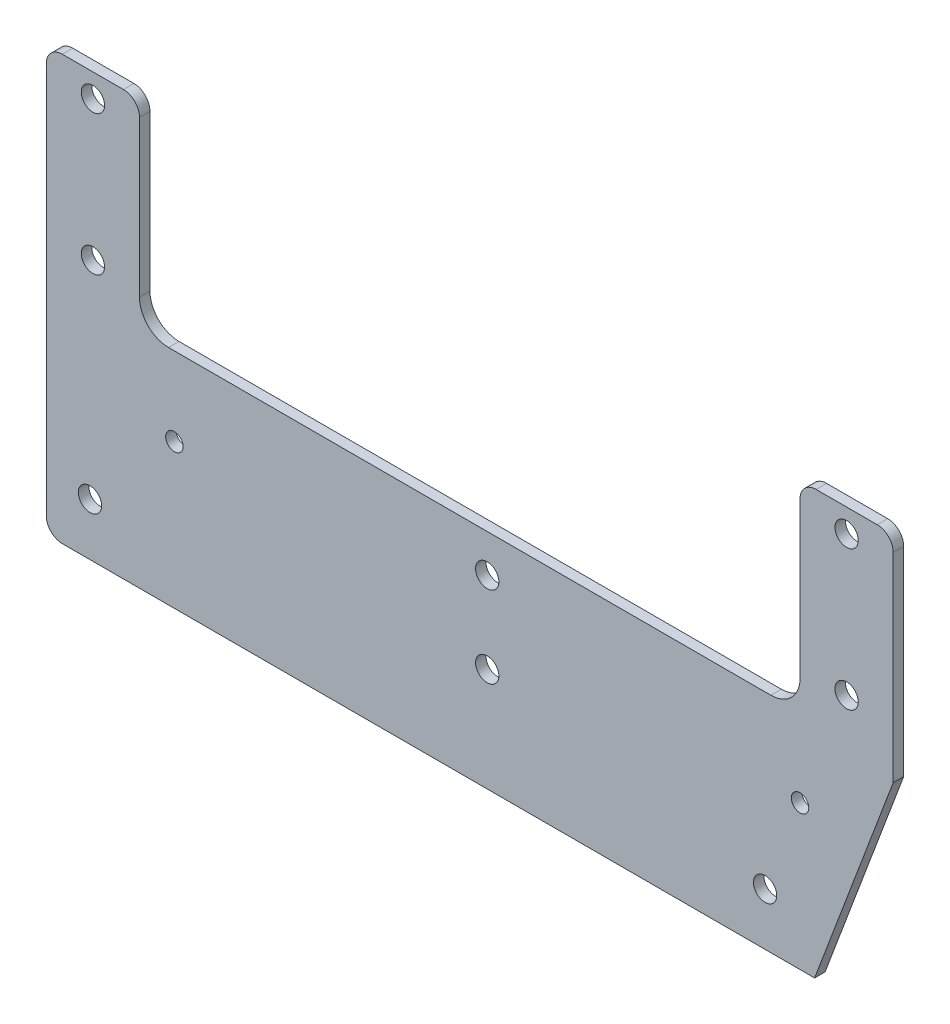
SolidWorks part; units mm, degrees
ref_plane "前视基准面" through (0, 0, 0) normal (0, 0, 1) x (1, 0, 0)
ref_plane "上视基准面" through (0, 0, 0) normal (0, 1, 0) x (1, 0, 0)
ref_plane "右视基准面" through (0, 0, 0) normal (1, 0, 0) x (0, 0, -1)
sketch "草图1" plane through (0, 0, 0) normal (0, 0, 1) x (1, 0, 0)
  line L0 (0, 0) -> (107.45, 0) construction
  line L1 (-22, -24.8) -> (109.95, -24.8)
  line L2 (115.45, 44) -> (115.45, 48) construction
  line L3 (109.95, -24.8) -> (123.45, 11)
  line L4 (123.45, 11) -> (123.45, 48)
  line L5 (123.45, 48) -> (107.45, 48)
  line L6 (107.45, 48) -> (107.45, 13.5)
  line L7 (107.45, 13.5) -> (-6, 13.5)
  line L8 (-6, 13.5) -> (-6, 48)
  line L9 (-6, 48) -> (-22, 48)
  line L10 (-22, 48) -> (-22, -24.8)
  line L11 (-14, 44) -> (-14, 48) construction
  line L12 (53.725, 7) -> (53.725, 0) construction
  circle A0 centre (0, 0) radius 1.5
  circle A1 centre (107.45, 0) radius 1.5
  circle A2 centre (115.45, 20) radius 2
  circle A3 centre (-14, 20) radius 2
  circle A4 centre (-14.5, -15.8) radius 2
  circle A5 centre (101.45, -15.8) radius 2
  circle A6 centre (115.45, 44) radius 2
  circle A7 centre (-14, 44) radius 2
  circle A8 centre (53.725, 7) radius 2
  circle A9 centre (53.725, -7) radius 2
  dimension "D2" = 4
  dimension "D7" = 3
  dimension "D1" = 107.45
  dimension "D3" = 20
  dimension "D4" = 14
  dimension "D5" = 8
  dimension "D6" = 14.5
  dimension "6" = 6
  dimension "D8" = 15.8
  dimension "D9" = 9
  dimension "D10" = 13.5
  dimension "D11" = 24
  dimension "D12" = 24
  dimension "D13" = 4
  dimension "D14" = 8
  dimension "D15" = 8
  dimension "D16" = 4
  dimension "D17" = 2.5
  dimension "D18" = 11
  dimension "D19" = 7
extrude "凸台-拉伸1" add sketch "草图1" along normal blind 1.8
fillet "圆角1" radius 2.75 5 edges at (123.45, 48, 0.9) (107.45, 48, 0.9) (-6, 48, 0.9) (-22, 48, 0.9) (-22, -24.8, 0.9)
fillet "圆角2" radius 5 2 edges at (-6, 13.5, 0.9) (107.45, 13.5, 0.9)
